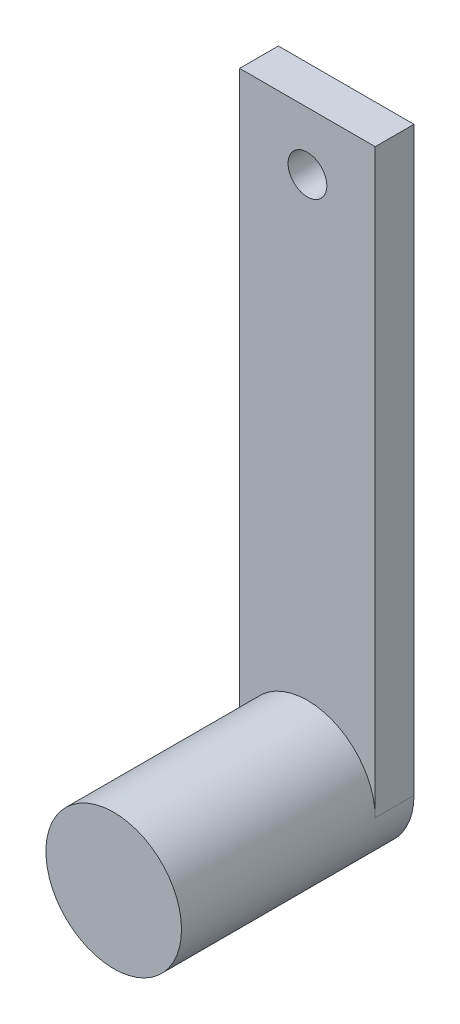
SolidWorks part; units mm, degrees
ref_plane "Front Plane" through (0, 0, 0) normal (0, 0, 1) x (1, 0, 0)
ref_plane "Top Plane" through (0, 0, 0) normal (0, 1, 0) x (1, 0, 0)
ref_plane "Right Plane" through (0, 0, 0) normal (1, 0, 0) x (0, 0, -1)
sketch "Sketch1" plane through (0, 0, 0) normal (0, 0, 1) x (1, 0, 0)
  circle A0 centre (0, 0) radius 3.5
  dimension "D1" = 7
extrude "Boss-Extrude1" add sketch "Sketch1" along normal blind 10
sketch "Sketch2" plane through (0, 0, 0) normal (0, 0, -1) x (-1, 0, 0)
  line L0 (-3.5, 0) -> (-3.5, 30)
  line L1 (-3.5, 30) -> (3.5, 30)
  line L2 (3.5, 30) -> (3.5, 0)
  line L3 (0, -1000) -> (0, 49000) construction
  circle A0 centre (0, 0) radius 3.5 construction
  arc A1 (-3.5, 0) -> (3.5, 0) centre (0, 0) ccw
  circle A2 centre (0, 27) radius 1
  dimension "D2" = 2
  dimension "D1" = 30
  dimension "D3" = 3
extrude "Boss-Extrude2" add sketch "Sketch2" along normal blind 2 contours L0 L1 L2 A1 | A2
